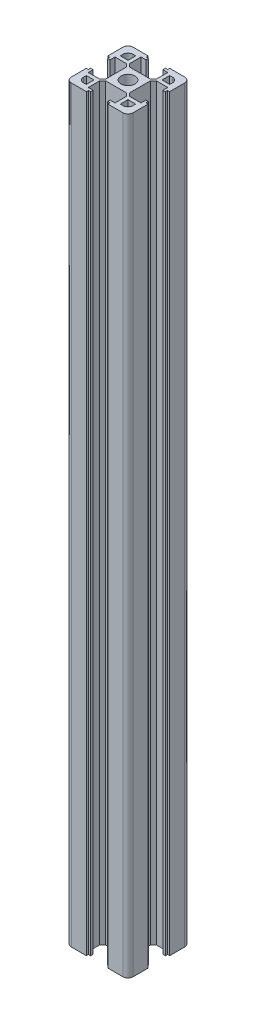
SolidWorks part; units mm, degrees
material "氧化铝"
ref_plane "前视基准面" through (0, 0, 0) normal (0, 0, 1) x (1, 0, 0)
ref_plane "上视基准面" through (0, 0, 0) normal (0, 1, 0) x (1, 0, 0)
ref_plane "右视基准面" through (0, 0, 0) normal (1, 0, 0) x (0, 0, -1)
sketch "草图1" plane through (0, 0, 0) normal (0, 1, 0) x (1, 0, 0)
  line L0 (-1000, 0) -> (49000, 0) construction
  line L1 (0, -1000) -> (0, 49000) construction
  line L2 (-12.8, 4.1) -> (-12.8, 6.4956)
  line L3 (-12.8, 6.4956) -> (-7.2734, 6.4956)
  line L4 (-7.2734, 6.4956) -> (-5.8, 5.0222)
  line L5 (-5.8, 5.0222) -> (-5.8, 0)
  line L6 (-12.8, 4.1) -> (-14, 4.1)
  line L7 (-14, 4.1) -> (-14, 5.2)
  line L8 (-14, 5.2) -> (-15, 5.2)
  line L9 (-15, 5.2) -> (-15, 12.5)
  line L10 (-12, 9.5) -> (-12, 8.25)
  line L11 (-12, 8.25) -> (-8.25, 8.25)
  line L12 (707.1068, -707.1068) -> (-34648.2323, 34648.2323) construction
  line L13 (-8.25, 12) -> (-8.25, 8.25)
  line L14 (-9.5, 12) -> (-8.25, 12)
  line L15 (-5.2, 15) -> (-12.5, 15)
  line L16 (-5.2, 14) -> (-5.2, 15)
  line L17 (-4.1, 14) -> (-5.2, 14)
  line L18 (-4.1, 12.8) -> (-4.1, 14)
  line L19 (-5.0222, 5.8) -> (0, 5.8)
  line L20 (-6.4956, 7.2734) -> (-5.0222, 5.8)
  line L21 (-6.4956, 12.8) -> (-6.4956, 7.2734)
  line L22 (-4.1, 12.8) -> (-6.4956, 12.8)
  line L23 (4.1, 12.8) -> (6.4956, 12.8)
  line L24 (6.4956, 12.8) -> (6.4956, 7.2734)
  line L25 (6.4956, 7.2734) -> (5.0222, 5.8)
  line L26 (5.0222, 5.8) -> (0, 5.8)
  line L27 (4.1, 12.8) -> (4.1, 14)
  line L28 (4.1, 14) -> (5.2, 14)
  line L29 (5.2, 14) -> (5.2, 15)
  line L30 (5.2, 15) -> (12.5, 15)
  line L31 (9.5, 12) -> (8.25, 12)
  line L32 (8.25, 12) -> (8.25, 8.25)
  line L33 (12, 8.25) -> (8.25, 8.25)
  line L34 (12, 9.5) -> (12, 8.25)
  line L35 (15, 5.2) -> (15, 12.5)
  line L36 (14, 5.2) -> (15, 5.2)
  line L37 (14, 4.1) -> (14, 5.2)
  line L38 (12.8, 4.1) -> (14, 4.1)
  line L39 (5.8, 5.0222) -> (5.8, 0)
  line L40 (7.2734, 6.4956) -> (5.8, 5.0222)
  line L41 (12.8, 6.4956) -> (7.2734, 6.4956)
  line L42 (12.8, 4.1) -> (12.8, 6.4956)
  line L43 (12.8, -4.1) -> (12.8, -6.4956)
  line L44 (12.8, -6.4956) -> (7.2734, -6.4956)
  line L45 (7.2734, -6.4956) -> (5.8, -5.0222)
  line L46 (5.8, -5.0222) -> (5.8, 0)
  line L47 (12.8, -4.1) -> (14, -4.1)
  line L48 (14, -4.1) -> (14, -5.2)
  line L49 (14, -5.2) -> (15, -5.2)
  line L50 (15, -5.2) -> (15, -12.5)
  line L51 (12, -9.5) -> (12, -8.25)
  line L52 (12, -8.25) -> (8.25, -8.25)
  line L53 (8.25, -12) -> (8.25, -8.25)
  line L54 (9.5, -12) -> (8.25, -12)
  line L55 (5.2, -15) -> (12.5, -15)
  line L56 (5.2, -14) -> (5.2, -15)
  line L57 (4.1, -14) -> (5.2, -14)
  line L58 (4.1, -12.8) -> (4.1, -14)
  line L59 (5.0222, -5.8) -> (0, -5.8)
  line L60 (6.4956, -7.2734) -> (5.0222, -5.8)
  line L61 (6.4956, -12.8) -> (6.4956, -7.2734)
  line L62 (4.1, -12.8) -> (6.4956, -12.8)
  line L63 (-4.1, -12.8) -> (-6.4956, -12.8)
  line L64 (-6.4956, -12.8) -> (-6.4956, -7.2734)
  line L65 (-6.4956, -7.2734) -> (-5.0222, -5.8)
  line L66 (-5.0222, -5.8) -> (0, -5.8)
  line L67 (-4.1, -12.8) -> (-4.1, -14)
  line L68 (-4.1, -14) -> (-5.2, -14)
  line L69 (-5.2, -14) -> (-5.2, -15)
  line L70 (-5.2, -15) -> (-12.5, -15)
  line L71 (-9.5, -12) -> (-8.25, -12)
  line L72 (-8.25, -12) -> (-8.25, -8.25)
  line L73 (-12, -8.25) -> (-8.25, -8.25)
  line L74 (-12, -9.5) -> (-12, -8.25)
  line L75 (-15, -5.2) -> (-15, -12.5)
  line L76 (-14, -5.2) -> (-15, -5.2)
  line L77 (-14, -4.1) -> (-14, -5.2)
  line L78 (-12.8, -4.1) -> (-14, -4.1)
  line L79 (-5.8, -5.0222) -> (-5.8, 0)
  line L80 (-7.2734, -6.4956) -> (-5.8, -5.0222)
  line L81 (-12.8, -6.4956) -> (-7.2734, -6.4956)
  line L82 (-12.8, -4.1) -> (-12.8, -6.4956)
  circle A0 centre (0, 0) radius 3.4
  arc A1 (-12, 9.5) -> (-9.5, 12) centre (-9.5, 9.5) cw
  arc A2 (-15, 12.5) -> (-12.5, 15) centre (-12.5, 12.5) cw
  arc A3 (9.5, 12) -> (12, 9.5) centre (9.5, 9.5) cw
  arc A4 (12.5, 15) -> (15, 12.5) centre (12.5, 12.5) cw
  arc A5 (12, -9.5) -> (9.5, -12) centre (9.5, -9.5) cw
  arc A6 (15, -12.5) -> (12.5, -15) centre (12.5, -12.5) cw
  arc A7 (-9.5, -12) -> (-12, -9.5) centre (-9.5, -9.5) cw
  arc A8 (-12.5, -15) -> (-15, -12.5) centre (-12.5, -12.5) cw
  point P32 (-12, 12)
  point P35 (-15, 15)
  point P114 (0, 0)
  dimension "D1" = 6.8
  dimension "D12" = 2.5
  dimension "D2" = 15
  dimension "D3" = 1.1
  dimension "D4" = 9.2
  dimension "D5" = 4.1
  dimension "D6" = 45
  dimension "D7" = 5.2
  dimension "D8" = 1
  dimension "D9" = 2.2
  dimension "D10" = 3.75
  dimension "D11" = 8.25
  dimension "D13" = 4
extrude "凸台-拉伸1" add sketch "草图1" along normal blind 363
